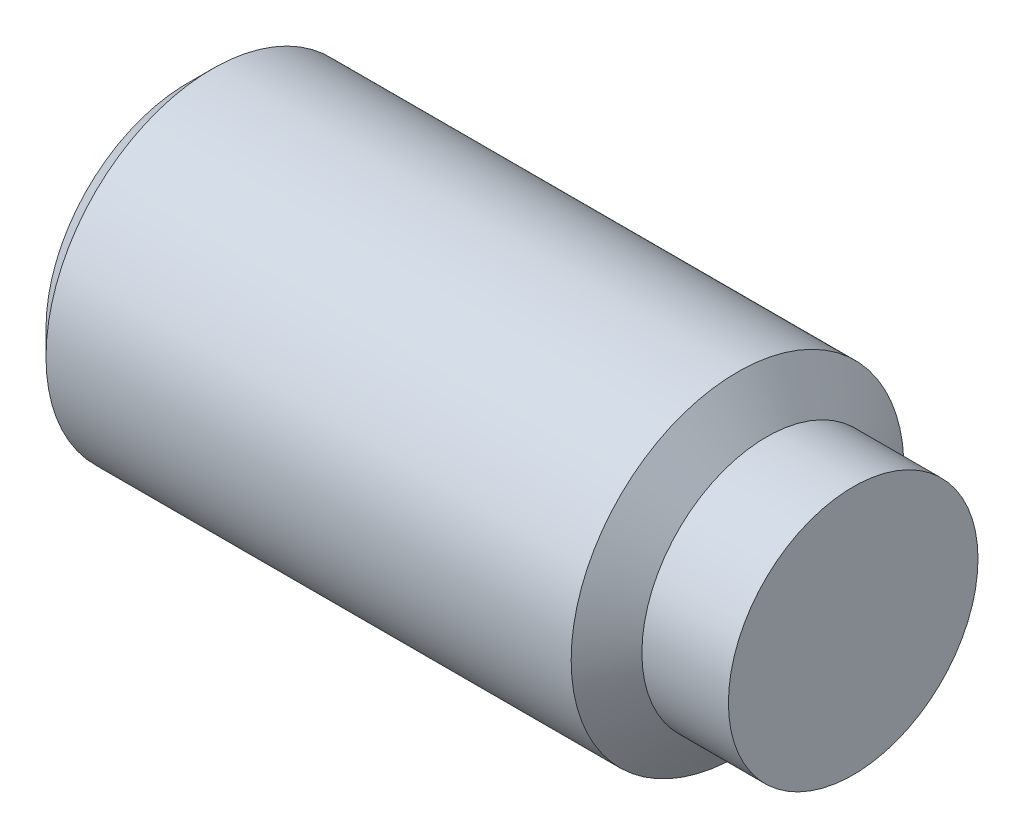
SolidWorks part; units mm, degrees
revolve "BaseBody" add sketch "BodySke" angle 360 about L5
sketch "BodySke" plane through (0, 0, 0) normal (0, 0, 1) x (1, 0, 0)
  line L0 (0, 0) -> (0, 10.8102)
  line L1 (0, 10.8102) -> (1.8898, 12.7)
  line L2 (1.8898, 12.7) -> (41.9728, 12.7)
  line L3 (41.9728, 12.7) -> (44.196, 9.525)
  line L4 (50.8, 0) -> (0, 0)
  line L5 (-12.7, 0) -> (88.9, 0) construction
  line L6 (44.196, 9.525) -> (50.8, 9.525)
  line L7 (50.8, 9.525) -> (50.8, 0)
  line L8 (0, -10.8102) -> (1.8898, -12.7) construction
  line L9 (44.196, -9.525) -> (50.8, -9.525) construction
  line L10 (2.1082, 15.875) -> (2.1082, -3.175) construction
  dimension "Diameter" = 25.4
  dimension "Drive_ch_ang" = 45
  dimension "Minor_dia" = 21.6205
  dimension "Dog_dia" = 19.05
  dimension "Dog_len" = 6.604
  dimension "Length" = 50.8
  dimension "D1" = 55
  dimension "Advance" = 2.1082
cosmetic thread "ThreadCosmetic" [suppressed] parameters "Thread_minor"=21.6205
ref_plane "Plane1" through (0, 0, 0) normal (0, 0, 1) x (1, 0, 0)
ref_plane "Plane2" through (0, 0, 0) normal (0, 1, 0) x (1, 0, 0)
ref_plane "Plane3" through (0, 0, 0) normal (1, 0, 0) x (0, 0, -1)
sketch "Sketch2" plane through (0, 0, 0) normal (-1, 0, 0) x (0, 0, 1)
  line L0 (4.1208, 7.1374) -> (-4.1208, 7.1374)
  line L1 (-4.1208, 7.1374) -> (-8.2416, 0)
  line L2 (4.1208, 7.1374) -> (8.2416, 0)
  line L3 (4.1208, -7.1374) -> (8.2416, 0)
  line L4 (4.1208, -7.1374) -> (-4.1208, -7.1374)
  line L5 (-4.1208, -7.1374) -> (-8.2416, 0)
  dimension "Hex_size" = 14.2748
  dimension "D2" = 7.1374
  dimension "D3" = 7.1374
extrude "Hex" cut sketch "Sketch2" against normal blind 14.2748
sketch "Sketch4" plane through (0, 4.7709, -0.5249) normal (-1, 0, 0) x (0, 0, 1)
  line L0 (0.5249, -4.7709) -> (10.6976, -4.7709)
  line L1 (0.5249, -4.7709) -> (6.6732, -1.2211) construction
  line L2 (0.5249, -4.7709) -> (5.6112, 4.0389)
  line L3 (8.9666, -2.6687) -> (10.2861, -1.9069)
  line L4 (6.5663, 1.4888) -> (7.8858, 2.2506)
  arc A0 (8.9666, -2.6687) -> (6.5663, 1.4888) centre (0.5249, -4.7709) ccw
  arc A1 (10.6976, -4.7709) -> (10.2861, -1.9069) centre (0.5249, -4.7709) ccw
  arc A2 (5.6112, 4.0389) -> (7.8858, 2.2506) centre (0.5249, -4.7709) cw
  circle A3 centre (0.5249, -4.7709) radius 8.6995 construction
  circle A4 centre (0.5249, -4.7709) radius 10.1727 construction
  dimension "Spline_n_dim" = 17.399
  dimension "Spline_m_dim" = 20.3454
  dimension "D1" = 30
  dimension "Spline_a_dim" = 60
  dimension "Spline_p_dim" = 4.8006
  dimension "D3" = 2.4003
extrude "Spline" [suppressed] cut sketch "Sketch4" against normal blind 12.7
pattern_circular "CirPattern1" [suppressed] count 6 every 60 about axis through (-12.7, 0, 0) along (1, 0, 0)
sketch "ThdSchSke" plane through (0, 0, 0) normal (0, 0, 1) x (1, 0, 0)
  line L0 (1.8898, -10.8102) -> (0.5665, -12.7)
  line L1 (1.8898, -10.8102) -> (3.213, -12.7)
  line L2 (3.213, -12.7) -> (3.213, -15.875)
  line L3 (-3.175, 0) -> (5.1513, 0) construction
  line L4 (1.8898, 12.7) -> (1.8898, -12.7) construction
  line L5 (3.213, -15.875) -> (0.5665, -15.875)
  line L6 (0.5665, -15.875) -> (0.5665, -12.7)
  dimension "Thread_minor" = 21.6205
  dimension "Diameter" = 25.4
revolve "ThreadSchematic" [suppressed] cut sketch "ThdSchSke" angle 360 about L3
pattern_linear "ThdSchPat" [suppressed]
equation "\"D2@Sketch2\" = \"Hex_size@Sketch2\" / 2"
equation "\"D3@Sketch2\" = \"Hex_size@Sketch2\" / 2"
equation "\"Thread_minor@ThreadCosmetic\" = \"Minor_dia@BodySke\""
equation "\"D1@Sketch4\" = \"Spline_a_dim@Sketch4\" / 2"
equation "\"D3@Sketch4\" = \"Spline_p_dim@Sketch4\" / 2"
equation "\"D2@CirPattern1\" = \"Spline_a_dim@Sketch4\""
equation "\"Num_teeth@CirPattern1\" = 360 / \"D2@CirPattern1\""
equation "\"Thread_minor@ThdSchSke\" = \"Thread_minor@ThreadCosmetic\""
equation "\"Diameter@ThdSchSke\" = \"Diameter@BodySke\""
equation "\"Overcut@ThdSchSke\" = \"Diameter@BodySke\" * 1.25"
equation "\"Num_threads@ThdSchPat\" = int( (\"Length@BodySke\" - ( ( ( \"Diameter@BodySke\" - \"Minor_dia@BodySke\" ) * 0.5 ) / tan( \"Drive_ch_ang@BodySke\" * 0.017453292 ) ) - \"Dog_len@BodySke\" ) / \"Advance@BodySke\" + 0.999 )  + 1"
equation "\"Advance@ThdSchPat\" = (\"Length@BodySke\" - ( ( ( \"Diameter@BodySke\" - \"Minor_dia@BodySke\" ) * 0.5 ) / tan( \"Drive_ch_ang@BodySke\" * 0.017453292 ) ) - \"Dog_len@BodySke\" ) /  (\"Num_threads@ThdSchPat\" - 1) 'relax it"
equation "\"Num_threads@ThdSchPat\" = \"Num_threads@ThdSchPat\" - sgn( \"Num_threads@ThdSchPat\" - 1) '---chamfered tips only---"
